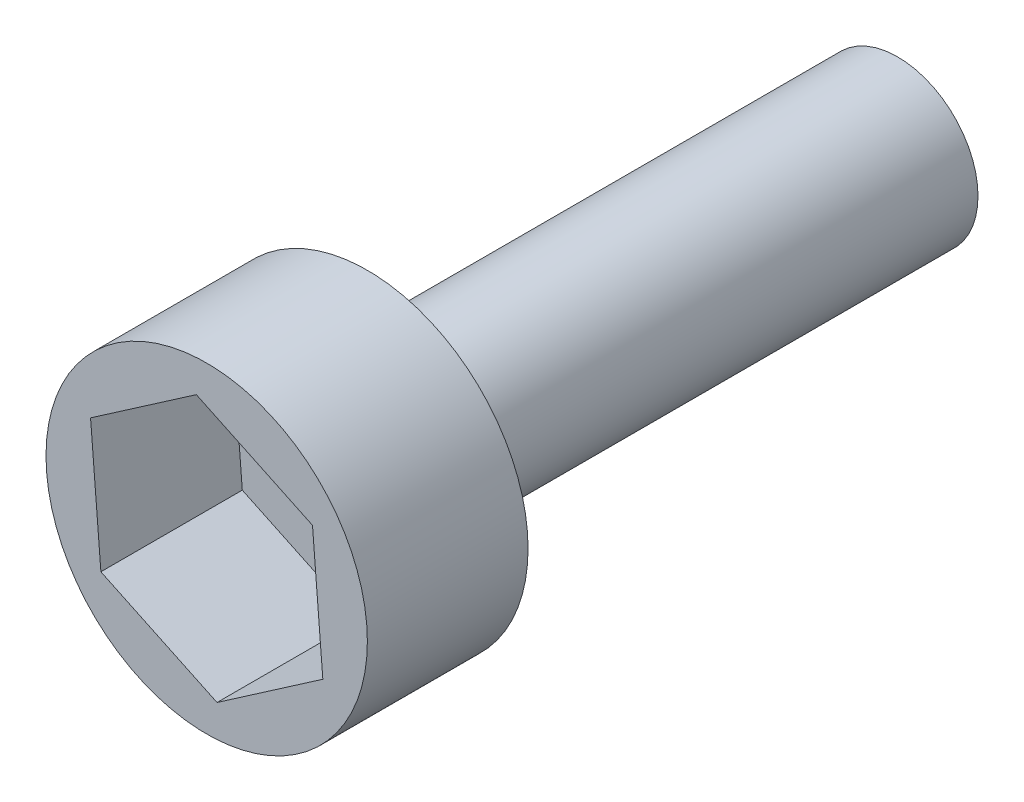
SolidWorks part; units mm, degrees
material "AISI 1020"
ref_plane "Alzado" through (0, 0, 0) normal (0, 0, 1) x (1, 0, 0)
ref_plane "Planta" through (0, 0, 0) normal (0, 1, 0) x (1, 0, 0)
ref_plane "Vista lateral" through (0, 0, 0) normal (1, 0, 0) x (0, 0, -1)
sketch "Croquis1" plane through (0, 0, 0) normal (0, 0, 1) x (1, 0, 0)
  circle A0 centre (0, 0) radius 1.5875
  dimension "D1" = 3.175
extrude "Saliente-Extruir1" add sketch "Croquis1" against normal blind 10.4775
sketch "Croquis2" plane through (0, 0, 0) normal (0, 0, 1) x (1, 0, 0)
  circle A0 centre (0, 0) radius 3.175
  dimension "D1" = 6.35
extrude "Saliente-Extruir2" add sketch "Croquis2" along normal blind 3.175
sketch "Croquis3" plane through (0, 0, 3.175) normal (0, 0, 1) x (1, 0, 0)
  line L1 (2.2947, -1.0891) -> (2.0905, 1.4427)
  line L2 (2.0905, 1.4427) -> (-0.2042, 2.5318)
  line L3 (-0.2042, 2.5318) -> (-2.2947, 1.0891)
  line L4 (-2.2947, 1.0891) -> (-2.0905, -1.4427)
  line L5 (-2.0905, -1.4427) -> (0.2042, -2.5318)
  line L6 (0.2042, -2.5318) -> (2.2947, -1.0891)
  circle A0 centre (0, 0) radius 2.1997 construction
  dimension "D1" = 2.54
extrude "Cortar-Extruir5" cut sketch "Croquis3" against normal blind 2.794
